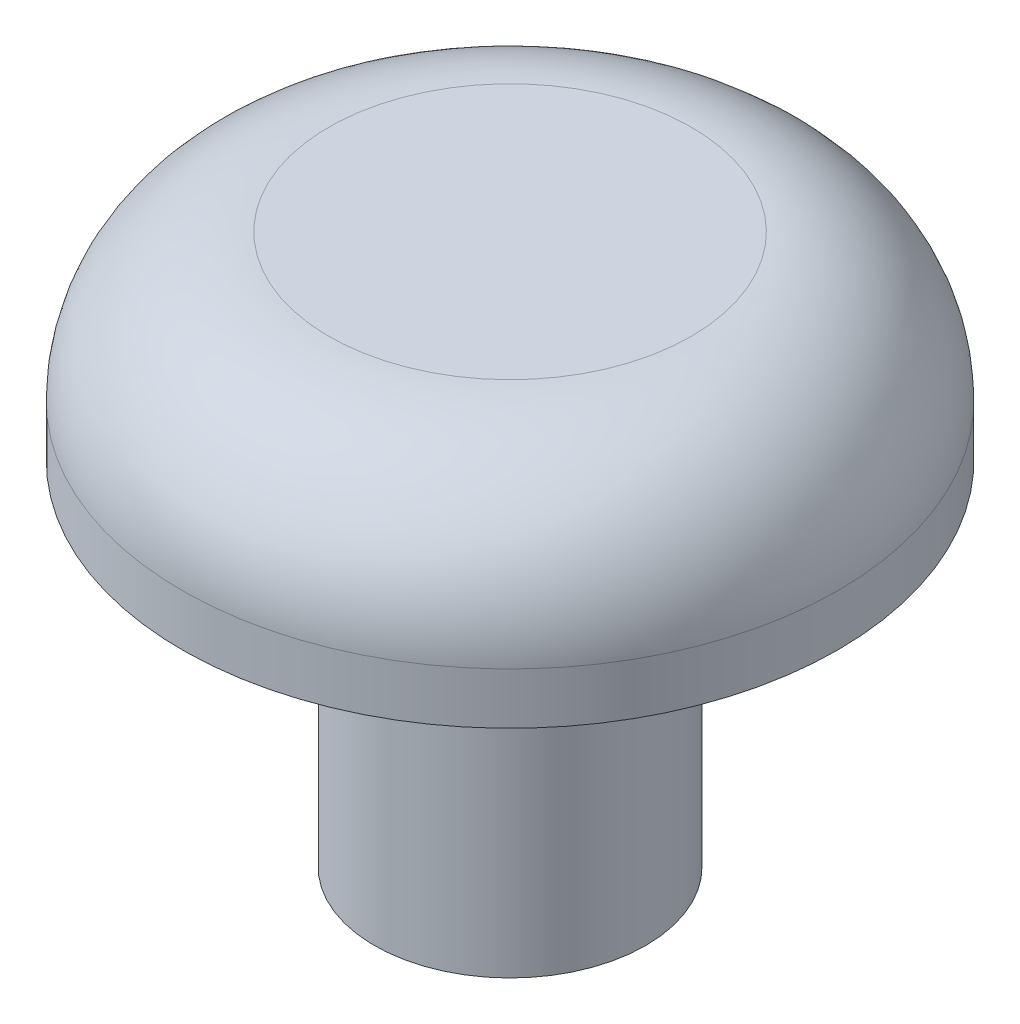
SolidWorks part; units mm, degrees
ref_plane "Front Plane" through (0, 0, 0) normal (0, 0, 1) x (1, 0, 0)
ref_plane "Top Plane" through (0, 0, 0) normal (0, 1, 0) x (1, 0, 0)
ref_plane "Right Plane" through (0, 0, 0) normal (1, 0, 0) x (0, 0, -1)
sketch "Sketch1" plane through (0, 0, 0) normal (0, 0, 1) x (1, 0, 0)
  line L0 (0, 0) -> (-5.6769, 0)
  line L1 (-5.6769, 0) -> (-5.6769, -3.429)
  line L2 (-5.6769, -3.429) -> (-2.3495, -3.429)
  line L3 (-2.3495, -3.429) -> (-2.3495, -9.525)
  line L4 (-2.3495, -9.525) -> (0, -9.525)
  line L5 (0, -9.525) -> (0, 0)
  dimension "D1" = 2.3495
  dimension "D2" = 5.6769
  dimension "D3" = 3.429
  dimension "D4" = 6.096
revolve "Revolve1" add sketch "Sketch1" angle 360 about L5
fillet "Fillet1" radius 2.54 1 edges at (5.6769, 0, 0)
hole_wizard "#6-32 Tapped Hole1" positions "Sketch3" profile "Sketch2" tap size "#6-32" standard "Ansi Inch"
sketch "Sketch3" plane through (0, -9.525, 0) normal (0, -1, 0) x (1, 0, 0)
  point P1 (0, 0)
sketch "Sketch2" plane through (0, -9.525, 0) normal (1, 0, 0) x (0, 0, -1)
  line L0 (0, 0) -> (0, 6.7055)
  line L1 (0, 6.7055) -> (1.3525, 5.8928)
  line L2 (1.3525, 5.8928) -> (1.3525, 0)
  line L5 (1.3525, 0) -> (0, 0)
  line L10 (0, 6.7055) -> (-1.3526, 5.8928) construction
  line L11 (0, -6.35) -> (0, 107.95) construction
  dimension "Tap Drill Dia." = 2.7051
  dimension "Tap Drill Depth" = 5.8928
  dimension "Drill Angle" = 118
cosmetic thread "Hole Thread1" parameters "D1"=5.8928, "D2"=3.5052
